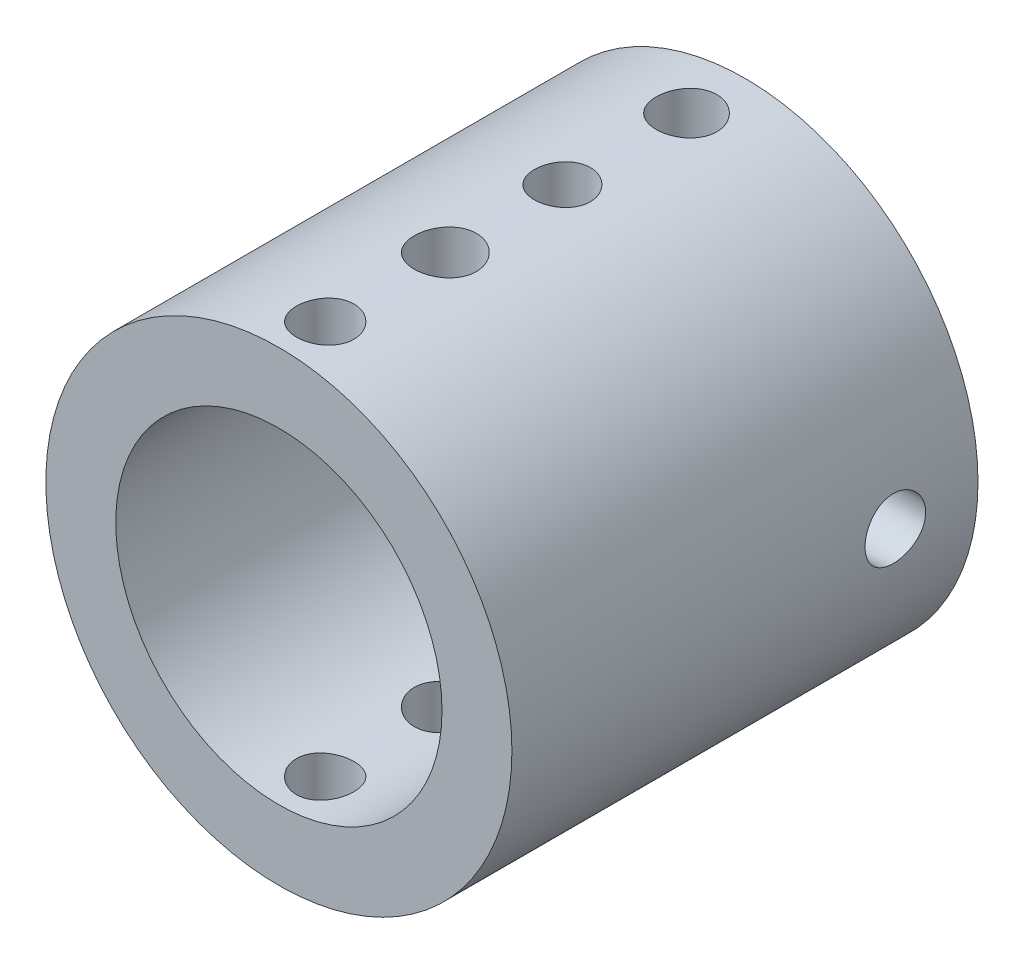
SolidWorks part; units mm, degrees
ref_plane "Plan de face" through (0, 0, 0) normal (0, 0, 1) x (1, 0, 0)
ref_plane "Plan de dessus" through (0, 0, 0) normal (0, 1, 0) x (1, 0, 0)
ref_plane "Plan de droite" through (0, 0, 0) normal (1, 0, 0) x (0, 0, -1)
sketch "Esquisse1" plane through (0, 0, 0) normal (0, 0, 1) x (1, 0, 0)
  circle A0 centre (0, 0) radius 15
  circle A1 centre (0, 0) radius 10.5
extrude "Boss.-Extru.1" add sketch "Esquisse1" along normal blind 30
sketch "Esquisse2" plane through (0, 0, 0) normal (0, 1, 0) x (1, 0, 0)
  circle A0 centre (0, -3.7617) radius 1.95
extrude "Enlèv. mat.-Extru.1" cut sketch "Esquisse2" against normal through all both and the other way through all
sketch "Esquisse3" plane through (0, 0, 0) normal (0, 1, 0) x (1, 0, 0)
  circle A0 centre (0, -11.7519) radius 1.8
extrude "Enlèv. mat.-Extru.2" cut sketch "Esquisse3" against normal through all both and the other way through all
sketch "Esquisse4" plane through (0, 0, 0) normal (0, 1, 0) x (1, 0, 0)
  circle A0 centre (0, -19.2874) radius 2
extrude "Enlèv. mat.-Extru.3" cut sketch "Esquisse4" against normal through all both and the other way through all
sketch "Esquisse5" plane through (0, 0, 0) normal (0, 1, 0) x (1, 0, 0)
  circle A0 centre (0, -27.0178) radius 1.85
extrude "Enlèv. mat.-Extru.4" cut sketch "Esquisse5" against normal through all both and the other way through all
sketch "Esquisse6" plane through (0, 0, 0) normal (1, 0, 0) x (0, 0, -1)
  circle A0 centre (-5.3208, 0) radius 1.95
extrude "Enlèv. mat.-Extru.5" cut sketch "Esquisse6" against normal through all both and the other way through all
